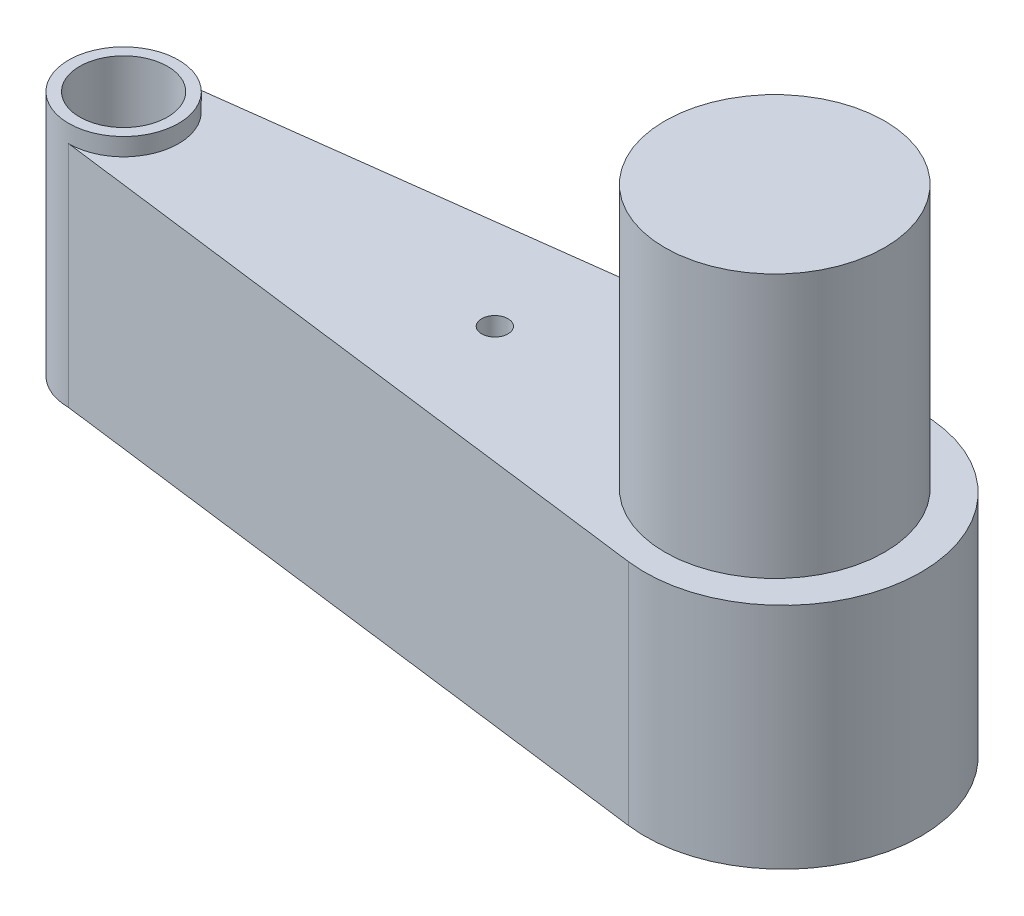
SolidWorks part; units mm, degrees
material "PE High Density"
ref_plane "Front Plane" through (0, 0, 0) normal (0, 0, 1) x (1, 0, 0)
ref_plane "Top Plane" through (0, 0, 0) normal (0, 1, 0) x (1, 0, 0)
ref_plane "Right Plane" through (0, 0, 0) normal (1, 0, 0) x (0, 0, -1)
sketch "Sketch1" plane through (0, 0, 0) normal (0, 1, 0) x (1, 0, 0)
  line L0 (-19.569, 0) -> (53.4391, 9.3326)
  line L1 (-19.569, -12.5) -> (53.4391, -21.8326)
  line L2 (71.1404, -6.25) -> (-25.819, -6.25) construction
  arc A0 (53.4391, 9.3326) -> (53.4391, -21.8326) centre (55.431, -6.25) cw
  arc A1 (-19.569, 0) -> (-19.569, -12.5) centre (-19.569, -6.25) ccw
  circle A2 centre (-19.569, -6.25) radius 5
  circle A3 centre (22.6607, -6.25) radius 1.5
  dimension "D1" = 6.25
  dimension "D2" = 10
  dimension "D4" = 3
  dimension "D3" = 75
extrude "Boss-Extrude2" add sketch "Sketch1" along normal blind 26
sketch "Sketch2" plane through (0, 26, 0) normal (0, 1, 0) x (1, 0, 0)
  line L0 (-19.569, 0) -> (-19.569, -12.5) construction
  arc A0 (-19.569, 0) -> (-19.569, -12.5) centre (-19.569, -6.25) ccw construction
  circle A1 centre (-19.569, -6.25) radius 6.25
extrude "Boss-Extrude3" add sketch "Sketch2" along normal blind 2
sketch "Sketch3" plane through (0, 28, 0) normal (0, 1, 0) x (1, 0, 0)
  circle A3 centre (-19.569, -6.25) radius 5
  circle A4 centre (-19.569, -6.25) radius 5
  dimension "D1" = 1.25
extrude "Cut-Extrude1" cut sketch "Sketch3" against normal blind 2
sketch "Sketch5" plane through (0, 26, 0) normal (0, 1, 0) x (1, 0, 0)
  circle A1 centre (54.5917, -6.3373) radius 12.5
  dimension "D1" = 25
extrude "Boss-Extrude4" add sketch "Sketch5" along normal blind 30
